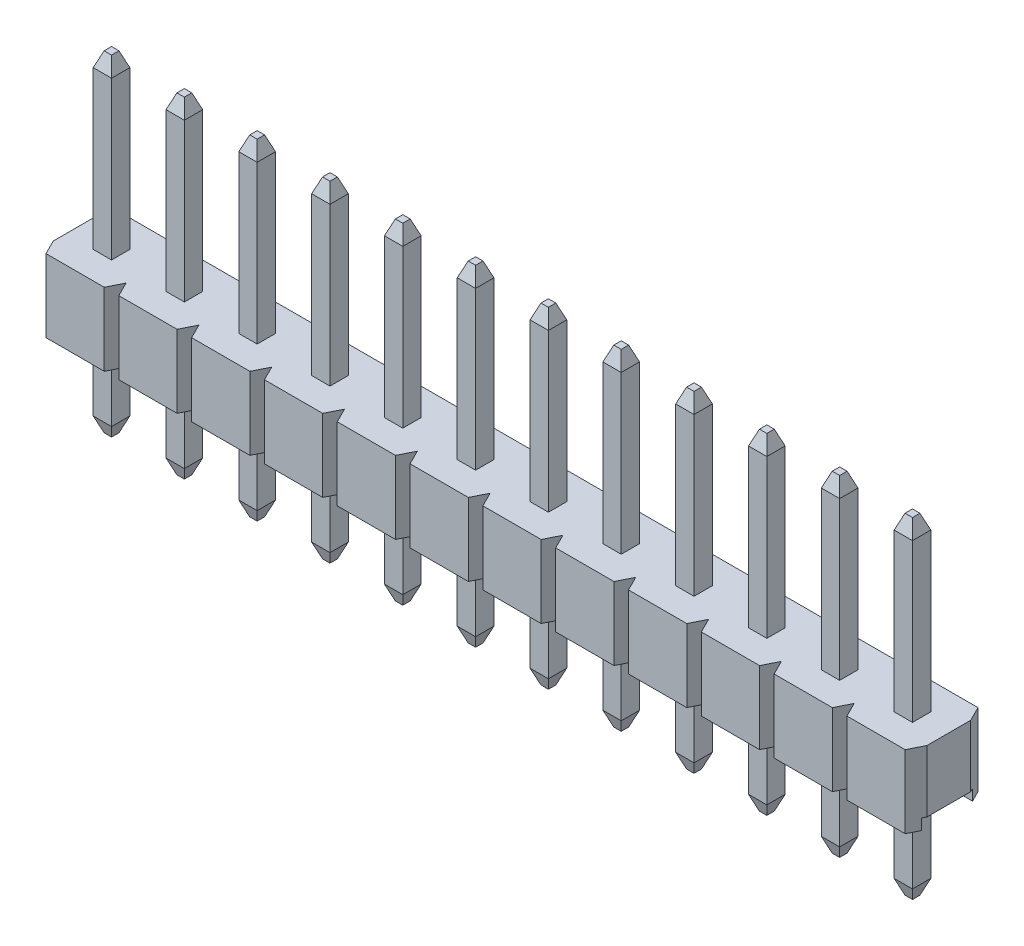
SolidWorks part; units mm, degrees
ref_plane "Front Plane" through (0, 0, 0) normal (0, 0, 1) x (1, 0, 0)
ref_plane "Top Plane" through (0, 0, 0) normal (0, 1, 0) x (1, 0, 0)
ref_plane "Right Plane" through (0, 0, 0) normal (1, 0, 0) x (0, 0, -1)
sketch "Sketch1" plane through (0, 0, 0) normal (0, 1, 0) x (1, 0, 0)
  line L1 (0, 0) -> (2.54, 0)
  line L2 (0, 0) -> (0, 2.54)
  line L3 (0, 2.54) -> (2.54, 2.54)
  line L4 (2.54, 0) -> (2.54, 2.54)
  dimension "D1" = 2.54
  dimension "D2" = 2.54
extrude "Main Body" add sketch "Sketch1" along normal blind 2.54
sketch "Sketch3" plane through (0, 0, 0) normal (-1, 0, 0) x (0, 0, 1)
  line L0 (-2.54, 0) -> (0, 0) construction
  line L1 (-2.159, 0) -> (-0.381, 0)
  line L2 (-2.159, 0) -> (-2.159, 0.381)
  line L3 (-2.159, 0.381) -> (-0.381, 0.381)
  line L4 (-0.381, 0) -> (-0.381, 0.381)
  line L5 (-2.54, 0) -> (-2.159, 0) construction
  line L6 (-0.381, 0) -> (0, 0) construction
  dimension "D1" = 0.381
extrude "Cut-Extrude1" cut sketch "Sketch3" against normal through all
sketch "Sketch4" plane through (0, 2.54, 0) normal (0, 1, 0) x (1, 0, 0)
  line L0 (0, 2.54) -> (0, 2.032)
  line L1 (0, 2.54) -> (0, 0) construction
  line L2 (0, 2.032) -> (0.254, 2.54)
  line L3 (2.54, 2.54) -> (0, 2.54) construction
  line L4 (0.254, 2.54) -> (0, 2.54)
  line L5 (2.54, 2.54) -> (2.286, 2.54)
  line L6 (2.286, 2.54) -> (2.54, 2.032)
  line L7 (2.54, 0) -> (2.54, 2.54) construction
  line L8 (2.54, 2.032) -> (2.54, 2.54)
  line L9 (2.54, 0) -> (2.286, 0)
  line L10 (0, 0) -> (2.54, 0) construction
  line L11 (2.286, 0) -> (2.54, 0.508)
  line L12 (2.54, 0.508) -> (2.54, 0)
  line L14 (0, 0) -> (0, 0.508)
  line L15 (0, 0.508) -> (0.254, 0)
  line L16 (0.254, 0) -> (0, 0)
  line M1 (0, 2.54) -> (0, 0)
  line M2 (0, 0) -> (2.54, 0)
  line M3 (2.54, 0) -> (2.54, 2.54)
  line M4 (2.54, 2.54) -> (0, 2.54)
  dimension "D1" = 0.254
  dimension "D2" = 0.508
extrude "Cut-Extrude2" cut sketch "Sketch4" against normal through all contours L2 M1 M4 | L6 M4 M3 | L15 M1 M2 | L9 L11 L12
pattern_linear "Body Pattern" count 12 spacing 2.54 along (-1, 0, 0) of "Main Body", "Cut-Extrude1", "Cut-Extrude2"
sketch "Sketch2" plane through (0, 2.54, 0) normal (0, 1, 0) x (1, 0, 0)
  line L0 (1.27, 2.54) -> (1.27, 1.59) construction
  line L1 (0.95, 0.95) -> (1.59, 0.95)
  line L2 (0.95, 0.95) -> (0.95, 1.59)
  line L3 (0.95, 1.59) -> (1.59, 1.59)
  line L4 (1.59, 0.95) -> (1.59, 1.59)
  line L6 (2.286, 2.54) -> (0.254, 2.54) construction
  line L8 (1.27, 0.95) -> (1.27, 0) construction
  line L9 (0.254, 0) -> (2.286, 0) construction
  dimension "D1" = 0.64
extrude "Pin" add sketch "Sketch2" along normal blind 6 and the other way offset from surface (5.54 mm away) 3 other way up to face at (1.27, 0, -0.1905)
chamfer "Chamfer1" distance 0.508 distance2 0.1905 4 edges at (0.95, 8.54, -1.27) (1.27, 8.54, -1.59) (1.59, 8.54, -1.27) (1.27, 8.54, -0.95)
chamfer "Chamfer2" distance 0.1905 distance2 0.508 4 edges at (1.27, -3, -1.59) (1.59, -3, -1.27) (1.27, -3, -0.95) (0.95, -3, -1.27)
pattern_linear "Pin Pattern" count 12 spacing 2.54 along (-1, 0, 0) of "Pin", "Chamfer1", "Chamfer2"
